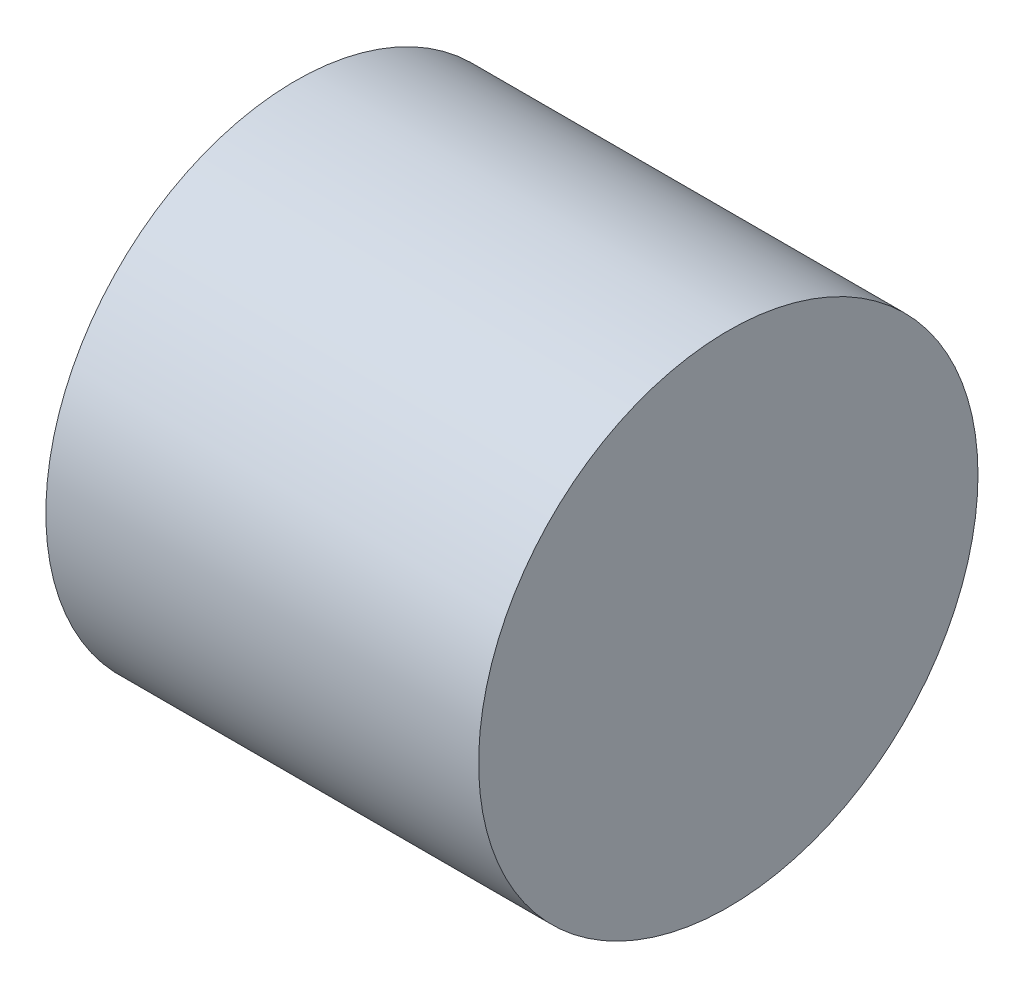
SolidWorks part; units mm, degrees
ref_plane "前视基准面" through (0, 0, 0) normal (0, 0, 1) x (1, 0, 0)
ref_plane "上视基准面" through (0, 0, 0) normal (0, 1, 0) x (1, 0, 0)
ref_plane "右视基准面" through (0, 0, 0) normal (1, 0, 0) x (0, 0, -1)
other "图形1"
other "图形 (闭合) -1"
sketch "草图1" plane through (0, 0, 0) normal (1, 0, 0) x (0, 0, -1)
  circle A0 centre (-21.3863, 21.0123) radius 5.7694
extrude "凸台-拉伸1" add sketch "草图1" along normal blind 10
